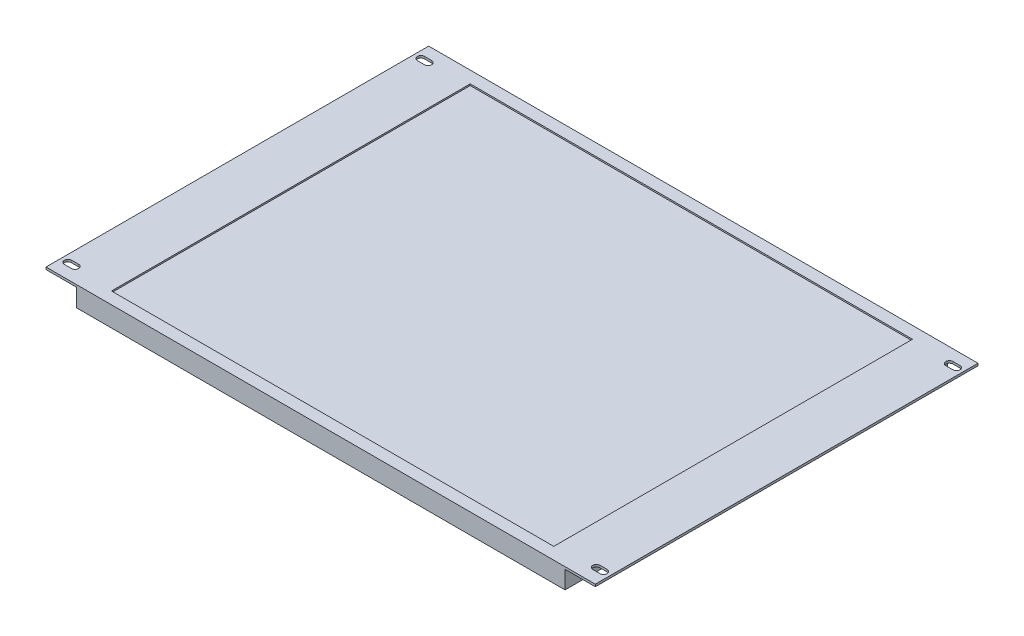
SolidWorks part; units mm, degrees
ref_plane "Front Plane" through (0, 0, 0) normal (0, 0, 1) x (1, 0, 0)
ref_plane "Top Plane" through (0, 0, 0) normal (0, 1, 0) x (1, 0, 0)
ref_plane "Right Plane" through (0, 0, 0) normal (1, 0, 0) x (0, 0, -1)
sketch "Sketch1" plane through (0, 0, 0) normal (0, 1, 0) x (1, 0, 0)
  line L1 (-163.5, 128) -> (163.5, 128)
  line L2 (-163.5, 128) -> (-163.5, -128)
  line L3 (-163.5, -128) -> (163.5, -128)
  line L4 (163.5, 128) -> (163.5, -128)
  line L5 (-163.5, 128) -> (163.5, -128) construction
  line L6 (-163.5, -128) -> (163.5, 128) construction
  point P0 (0, 0)
  dimension "D1" = 327
  dimension "D2" = 256
extrude "Boss-Extrude1" add sketch "Sketch1" along normal blind 13.462
sketch "Sketch2" plane through (0, 13.462, 0) normal (0, -1, 0) x (1, 0, 0)
  line L0 (-163.5, 128) -> (163.5, 128) construction
  line L1 (163.5, 128) -> (183.75, 128)
  line L2 (163.5, 128) -> (163.5, -128)
  line L3 (163.5, -128) -> (183.75, -128)
  line L4 (183.75, 128) -> (183.75, -128)
  line L5 (-163.5, -128) -> (-183.75, -128)
  line L6 (-163.5, -128) -> (-163.5, 128)
  line L7 (-163.5, 128) -> (-183.75, 128)
  line L8 (-183.75, -128) -> (-183.75, 128)
  line L9 (163.5, -128) -> (-163.5, -128) construction
  dimension "D1" = 367.5
extrude "Boss-Extrude2" add sketch "Sketch2" along normal blind 1.5
sketch "Sketch3" plane through (0, 13.462, 0) normal (0, 1, 0) x (1, 0, 0)
  line L0 (183.75, 128) -> (-183.75, 128) construction
  line L1 (-147.9535, 120) -> (147.9535, 120)
  line L2 (-147.9535, 120) -> (-147.9535, -120)
  line L3 (-147.9535, -120) -> (147.9535, -120)
  line L4 (147.9535, 120) -> (147.9535, -120)
  line L5 (-147.9535, 120) -> (147.9535, -120) construction
  line L6 (-147.9535, -120) -> (147.9535, 120) construction
  point P0 (0, 0)
  dimension "D1" = 381
  dimension "D2" = 8
extrude "Cut-Extrude1" cut sketch "Sketch3" against normal blind 1
sketch "Sketch4" plane through (0, 0, 0) normal (0, -1, 0) x (1, 0, 0)
  line L0 (163.5, -128) -> (-163.5, -128) construction
  line L1 (-143.5, -23) -> (-3.5, -23)
  line L2 (-143.5, -23) -> (-143.5, -83)
  line L3 (-143.5, -83) -> (-3.5, -83)
  line L4 (-3.5, -23) -> (-3.5, -83)
  line L5 (-143.5, -23) -> (-3.5, -83) construction
  line L6 (-143.5, -83) -> (-3.5, -23) construction
  line L9 (13.5, -4) -> (133.5, -4)
  line L10 (13.5, -4) -> (13.5, -34)
  line L11 (13.5, -34) -> (133.5, -34)
  line L12 (133.5, -4) -> (133.5, -34)
  line L13 (13.5, -4) -> (133.5, -34) construction
  line L14 (13.5, -34) -> (133.5, -4) construction
  line L15 (23.5, -55) -> (127.5, -55)
  line L16 (23.5, -55) -> (23.5, -78)
  line L17 (23.5, -78) -> (127.5, -78)
  line L18 (127.5, -55) -> (127.5, -78)
  line L19 (23.5, -55) -> (127.5, -78) construction
  line L20 (23.5, -78) -> (127.5, -55) construction
  line L21 (-163.5, -128) -> (-163.5, 128) construction
  line L22 (163.5, 128) -> (163.5, -128) construction
  line L23 (163.5, 128) -> (163.5, -128) construction
  point P0 (-73.5, -53)
  point P9 (73.5, -19)
  point P14 (75.5, -66.5)
  dimension "D1" = 105
  dimension "D2" = 160
  dimension "D3" = 140
  dimension "D4" = 60
  dimension "D5" = 150
  dimension "D6" = 120
  dimension "D7" = 124
  dimension "D8" = 30
  dimension "D9" = 140
  dimension "D10" = 73
  dimension "D11" = 23
  dimension "D12" = 104
extrude "Boss-Extrude4" add sketch "Sketch4" along normal blind 20
sketch "Sketch5" plane through (0, 13.462, 0) normal (0, 1, 0) x (1, 0, 0)
  line L0 (174.375, 118.225) -> (179.125, 118.225) construction
  line L1 (174.375, 120.65) -> (179.125, 120.65)
  line L2 (174.375, 115.8) -> (179.125, 115.8)
  line L3 (-179.125, 118.225) -> (-174.375, 118.225) construction
  line L4 (-179.125, 120.65) -> (-174.375, 120.65)
  line L5 (-179.125, 115.8) -> (-174.375, 115.8)
  line L6 (-179.125, -117.925) -> (-174.375, -117.925) construction
  line L7 (-179.125, -115.5) -> (-174.375, -115.5)
  line L8 (-179.125, -120.35) -> (-174.375, -120.35)
  line L9 (174.375, -117.925) -> (179.125, -117.925) construction
  line L10 (174.375, -115.5) -> (179.125, -115.5)
  line L11 (174.375, -120.35) -> (179.125, -120.35)
  line L12 (-176.75, 118.225) -> (-176.75, -117.925) construction
  line L13 (-176.75, -117.925) -> (176.75, -117.925) construction
  line L14 (176.75, -117.925) -> (176.75, 118.225) construction
  line L15 (176.75, 118.225) -> (-176.75, 118.225) construction
  line L19 (183.75, 128) -> (-183.75, 128) construction
  line L20 (183.75, 128) -> (183.75, -128) construction
  line L21 (-183.75, -128) -> (-183.75, 128) construction
  arc A0 (174.375, 120.65) -> (174.375, 115.8) centre (174.375, 118.225) ccw
  arc A1 (179.125, 115.8) -> (179.125, 120.65) centre (179.125, 118.225) ccw
  arc A2 (-179.125, 120.65) -> (-179.125, 115.8) centre (-179.125, 118.225) ccw
  arc A3 (-174.375, 115.8) -> (-174.375, 120.65) centre (-174.375, 118.225) ccw
  arc A4 (-179.125, -115.5) -> (-179.125, -120.35) centre (-179.125, -117.925) ccw
  arc A5 (-174.375, -120.35) -> (-174.375, -115.5) centre (-174.375, -117.925) ccw
  arc A6 (174.375, -115.5) -> (174.375, -120.35) centre (174.375, -117.925) ccw
  arc A7 (179.125, -120.35) -> (179.125, -115.5) centre (179.125, -117.925) ccw
  point P2 (176.75, 118.225)
  point P8 (-176.75, 118.225)
  point P15 (-176.75, -117.925)
  point P22 (176.75, -117.925)
  point P35 (-171.95, 118.225)
  point P36 (-181.55, 118.225)
  point P37 (181.55, 118.225)
  dimension "D1" = 7.35
  dimension "D2" = 241
  dimension "D3" = 9.6
  dimension "D4" = 4.85
  dimension "D5" = 2.2
  dimension "D6" = 2.2
  dimension "D7" = 9.775
  dimension "D8" = 236.15
extrude "Cut-Extrude2" cut sketch "Sketch5" against normal through all
